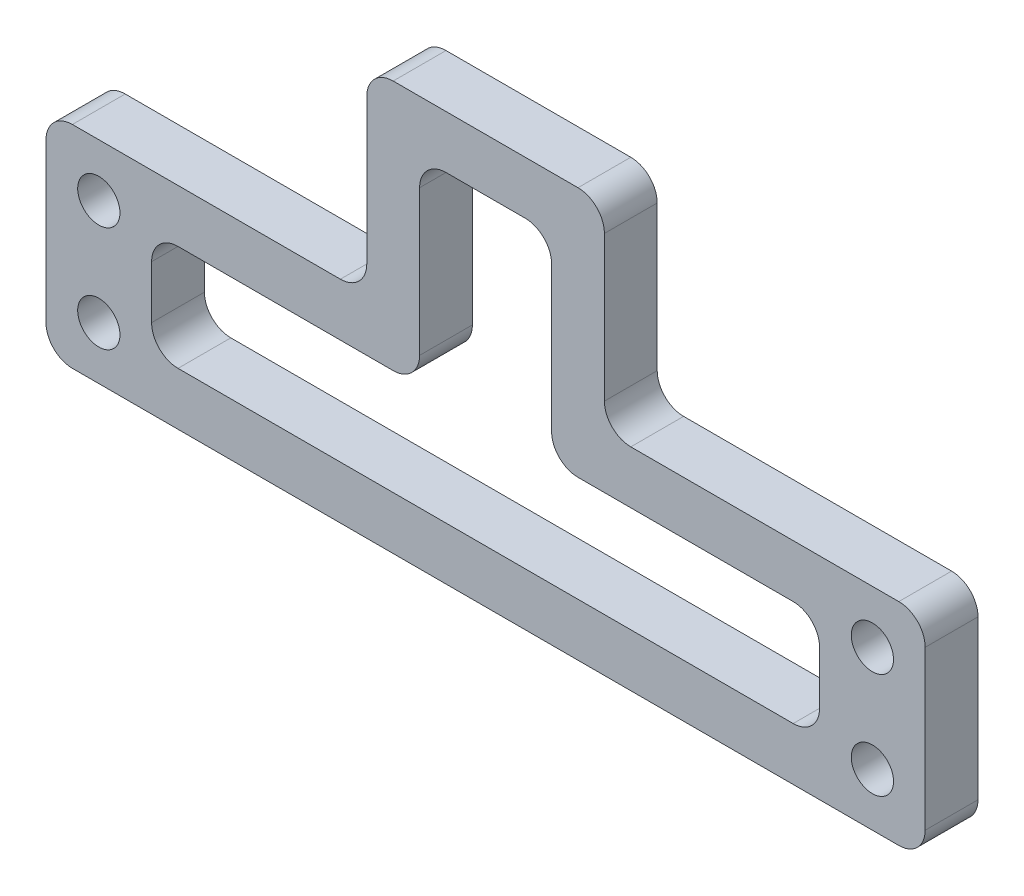
SolidWorks part; units mm, degrees
material "ABS"
ref_plane "前视基准面" through (0, 0, 0) normal (0, 0, 1) x (1, 0, 0)
ref_plane "上视基准面" through (0, 0, 0) normal (0, 1, 0) x (1, 0, 0)
ref_plane "右视基准面" through (0, 0, 0) normal (1, 0, 0) x (0, 0, -1)
sketch "草图1" plane through (0, 0, 0) normal (0, 0, 1) x (1, 0, 0)
  line L0 (0, 0) -> (66.6, 0)
  line L1 (66.6, 0) -> (66.6, 16)
  line L2 (66.6, 16) -> (42.3, 16)
  line L3 (0, 16) -> (0, 0)
  line L4 (33.3, 0) -> (33.3, 45.6952) construction
  line L5 (24.3, 16) -> (24.3, 31)
  line L6 (24.3, 31) -> (42.3, 31)
  line L7 (42.3, 31) -> (42.3, 16)
  line L8 (24.3, 16) -> (0, 16)
  line L9 (8, 12) -> (28.3, 12)
  line L10 (28.3, 12) -> (28.3, 27)
  line L11 (28.3, 27) -> (38.3, 27)
  line L12 (8, 12) -> (8, 4)
  line L13 (8, 4) -> (58.6, 4)
  line L14 (58.6, 12) -> (58.6, 4)
  line L15 (58.6, 12) -> (38.3, 12)
  line L16 (38.3, 12) -> (38.3, 27)
  circle A0 centre (4, 4) radius 1.6
  circle A1 centre (4, 12) radius 1.6
  circle A2 centre (62.6, 12) radius 1.6
  circle A3 centre (62.6, 4) radius 1.6
  point P26 (33.3, 4)
  point P29 (33.3, 27)
  dimension "D6" = 3.2
  dimension "D9" = 3.2
  dimension "D1" = 66.6
  dimension "D2" = 16
  dimension "D3" = 9
  dimension "D4" = 9
  dimension "D5" = 31
  dimension "D7" = 29.3
  dimension "D8" = 4
  dimension "D10" = 8
  dimension "D11" = 4
  dimension "D12" = 8
  dimension "D13" = 4
  dimension "D14" = 4
  dimension "D15" = 4
extrude "凸台-拉伸1" add sketch "草图1" along normal blind 4
fillet "圆角1" radius 2 16 edges at (66.6, 0, 2) (66.6, 16, 2) (42.3, 16, 2) (42.3, 31, 2) (24.3, 31, 2) (24.3, 16, 2) (58.6, 4, 2) (58.6, 12, 2) (38.3, 12, 2) (38.3, 27, 2) (28.3, 27, 2) (28.3, 12, 2) (8, 4, 2) (8, 12, 2) (0, 0, 2) (0, 16, 2)
